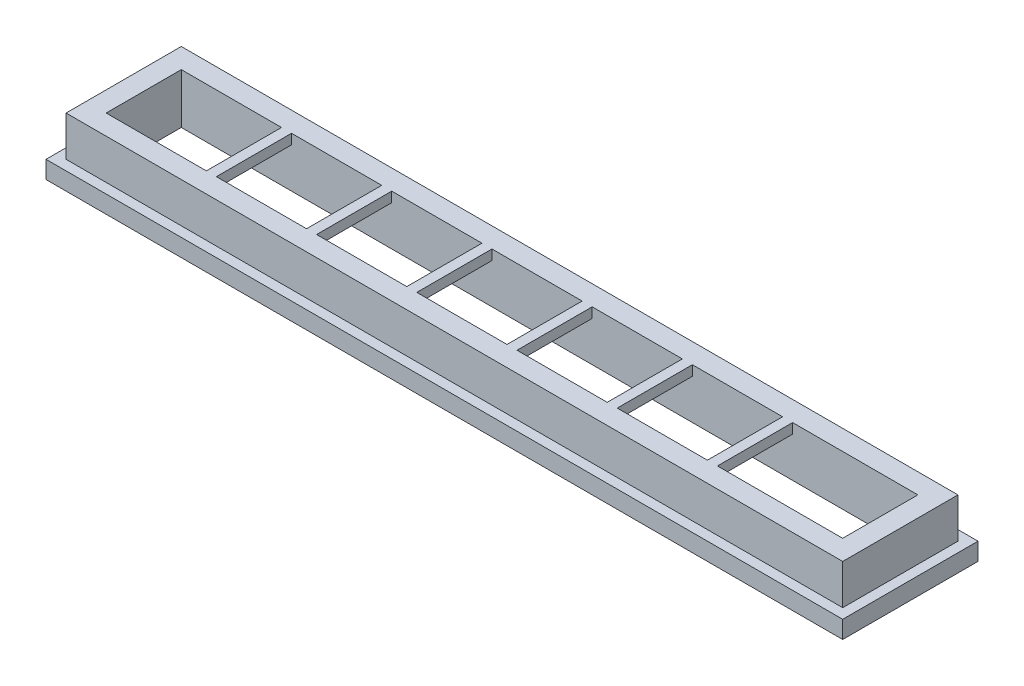
SolidWorks part; units mm, degrees
ref_plane "Ebene vorne" through (0, 0, 0) normal (0, 0, 1) x (1, 0, 0)
ref_plane "Ebene oben" through (0, 0, 0) normal (0, 1, 0) x (1, 0, 0)
ref_plane "Ebene rechts" through (0, 0, 0) normal (1, 0, 0) x (0, 0, -1)
sketch "Skizze1" plane through (0, 0, 0) normal (0, 1, 0) x (1, 0, 0)
  line L1 (-77.5, -11.5) -> (77.5, -11.5)
  line L2 (-77.5, -11.5) -> (-77.5, 11.5)
  line L3 (-77.5, 11.5) -> (77.5, 11.5)
  line L4 (77.5, -11.5) -> (77.5, 11.5)
  line L5 (-77.5, -11.5) -> (77.5, 11.5) construction
  line L6 (-77.5, 11.5) -> (77.5, -11.5) construction
  line L7 (-73.5, -7.5) -> (73.5, -7.5)
  line L8 (-73.5, -7.5) -> (-73.5, 7.5)
  line L9 (-73.5, 7.5) -> (73.5, 7.5)
  line L10 (73.5, -7.5) -> (73.5, 7.5)
  line L11 (-73.5, -7.5) -> (73.5, 7.5) construction
  line L12 (-73.5, 7.5) -> (73.5, -7.5) construction
  point P0 (0, 0)
  point P6 (0, 0)
  dimension "D1" = 4
  dimension "D2" = 4
  dimension "D3" = 155
  dimension "D4" = 23
extrude "Aufsatz-Linear austragen1" add sketch "Skizze1" along normal blind 10
sketch "Skizze2" plane through (0, 10, 0) normal (0, 1, 0) x (1, 0, 0)
  line L0 (73.5, 7.5) -> (-73.5, 7.5) construction
  line L1 (-53.5, 7.5) -> (-51.5, 7.5)
  line L2 (-53.5, 7.5) -> (-53.5, -7.5)
  line L3 (-53.5, -7.5) -> (-51.5, -7.5)
  line L4 (-51.5, 7.5) -> (-51.5, -7.5)
  line L5 (-73.5, -7.5) -> (73.5, -7.5) construction
  line L6 (-73.5, 7.5) -> (-73.5, -7.5) construction
  line L7 (-33.5, 7.5) -> (-31.5, 7.5)
  line L8 (-33.5, 7.5) -> (-33.5, -7.5)
  line L9 (-33.5, -7.5) -> (-31.5, -7.5)
  line L10 (-31.5, 7.5) -> (-31.5, -7.5)
  line L11 (-13.5, 7.5) -> (-11.5, 7.5)
  line L12 (-13.5, 7.5) -> (-13.5, -7.5)
  line L13 (-13.5, -7.5) -> (-11.5, -7.5)
  line L14 (-11.5, 7.5) -> (-11.5, -7.5)
  line L15 (6.5, 7.5) -> (8.5, 7.5)
  line L16 (6.5, 7.5) -> (6.5, -7.5)
  line L17 (6.5, -7.5) -> (8.5, -7.5)
  line L18 (8.5, 7.5) -> (8.5, -7.5)
  line L19 (26.5, 7.5) -> (28.5, 7.5)
  line L20 (26.5, 7.5) -> (26.5, -7.5)
  line L21 (26.5, -7.5) -> (28.5, -7.5)
  line L22 (28.5, 7.5) -> (28.5, -7.5)
  line L23 (46.5, 7.5) -> (48.5, 7.5)
  line L24 (46.5, 7.5) -> (46.5, -7.5)
  line L25 (46.5, -7.5) -> (48.5, -7.5)
  line L26 (48.5, 7.5) -> (48.5, -7.5)
  dimension "D1" = 2
  dimension "D2" = 20
  dimension "D4" = 18
  dimension "D3" = 6
extrude "Aufsatz-Linear austragen2" add sketch "Skizze2" against normal blind 2
sketch "Skizze3" plane through (0, 0, 0) normal (0, -1, 0) x (1, 0, 0)
  line L0 (79.5, -13.5) -> (79.5, 13.5)
  line L1 (79.5, 13.5) -> (-79.5, 13.5)
  line L2 (-79.5, 13.5) -> (-79.5, -13.5)
  line L3 (-79.5, -13.5) -> (79.5, -13.5)
  line L4 (77.5, -11.5) -> (77.5, 11.5)
  line L5 (77.5, 11.5) -> (-77.5, 11.5)
  line L6 (-77.5, 11.5) -> (-77.5, -11.5)
  line L7 (-77.5, -11.5) -> (77.5, -11.5)
  line L8 (77.5, -11.5) -> (77.5, 11.5)
  line L9 (77.5, 11.5) -> (-77.5, 11.5)
  line L10 (-77.5, 11.5) -> (-77.5, -11.5)
  line L11 (-77.5, -11.5) -> (77.5, -11.5)
  dimension "D1" = 0
  dimension "D2" = 2
extrude "Aufsatz-Linear austragen3" add sketch "Skizze3" along normal blind 1.5 and the other way blind 2
